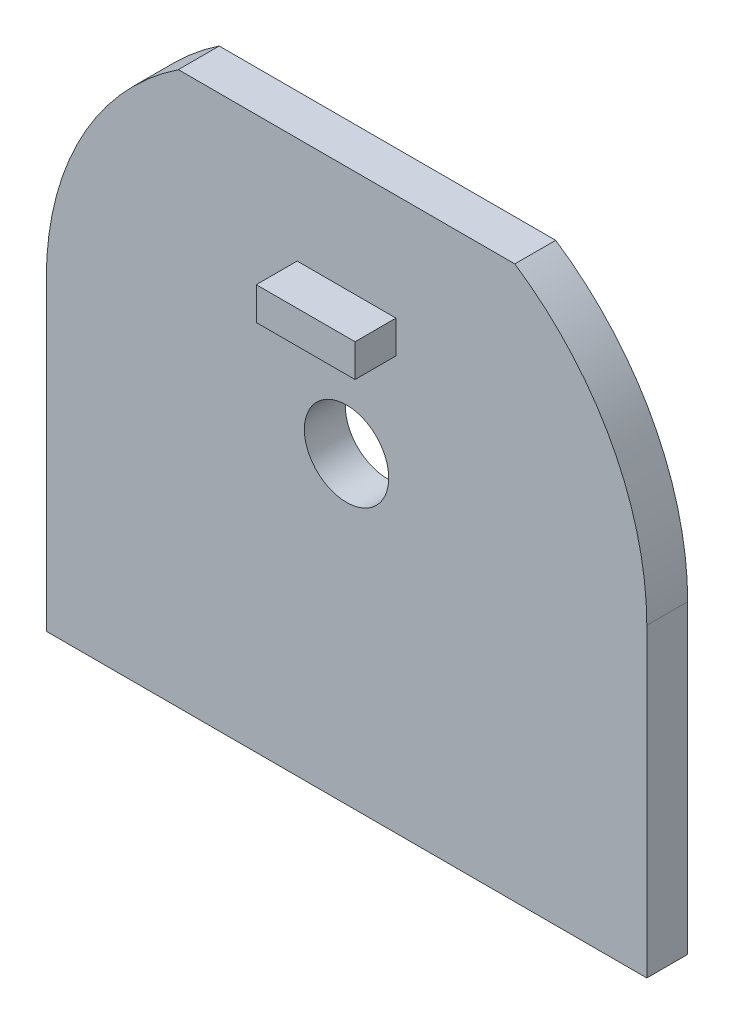
SolidWorks part; units mm, degrees
ref_plane "Front Plane" through (0, 0, 0) normal (0, 0, 1) x (1, 0, 0)
ref_plane "Top Plane" through (0, 0, 0) normal (0, 1, 0) x (1, 0, 0)
ref_plane "Right Plane" through (0, 0, 0) normal (1, 0, 0) x (0, 0, -1)
sketch "Sketch1" plane through (0, 0, 0) normal (0, 0, 1) x (1, 0, 0)
  line L0 (-5.8, 0.6) -> (-5.8, -5.3)
  line L1 (5.8, -5.3) -> (-5.8, -5.3)
  line L5 (5.8, -5.3) -> (-4.5581, 4.1652) construction
  line L6 (4.5581, 4.1652) -> (-5.8, -5.3) construction
  line L7 (5.8, 0.6) -> (5.8, -5.3)
  line L8 (-3.25, 5.3712) -> (3.25, 5.3712)
  line L9 (0, -1000) -> (0, 49000) construction
  circle A0 centre (0, 0.5712) radius 0.815
  arc A1 (-5.8, 0.6) -> (-3.25, 5.3712) centre (-0.0615, 0.6) cw
  arc A2 (5.8, 0.6) -> (3.25, 5.3712) centre (0.0615, 0.6) ccw
  point P0 (0, 0)
  point P8 (-3.25, 5.3712)
  point P9 (3.25, 5.3712)
  point P11 (-5.8, 0.6)
  point P12 (5.8, 0.6)
  point P19 (0, 5.3712)
  point P21 (0, 0)
  point P22 (0, 0)
  point P23 (0, 0)
  point P24 (0, 0)
  point P25 (0, 0)
  dimension "D3" = 1.63
  dimension "D1" = 11.6
  dimension "D7" = 5.9
  dimension "D2" = 6.5
  dimension "D4" = 5.3
  dimension "D5" = 5.3712
  dimension "D6" = 4.8
extrude "Boss-Extrude1" add sketch "Sketch1" along normal blind 0.79
sketch "Sketch2" plane through (0, 0, 0.79) normal (0, 0, 1) x (1, 0, 0)
  line L1 (-0.9541, 2.6836) -> (0.9541, 2.6836)
  line L2 (-0.9541, 2.6836) -> (-0.9541, 3.3164)
  line L3 (-0.9541, 3.3164) -> (0.9541, 3.3164)
  line L4 (0.9541, 2.6836) -> (0.9541, 3.3164)
  line L5 (-0.9541, 2.6836) -> (0.9541, 3.3164) construction
  line L6 (-0.9541, 3.3164) -> (0.9541, 2.6836) construction
  point P0 (0, 3)
  point P5 (0, 0)
  point P7 (0, 0)
  point P8 (0, 0)
  point P9 (0.9541, 2.3656)
  dimension "D1" = 3
  dimension "D2" = 1.9081
  dimension "D3" = 0.6328
extrude "Boss-Extrude2" add sketch "Sketch2" along normal blind 0.79
equation "\"D7@Sketch1\"=5.9mm"
equation "\"D2@Sketch1\"=6.5mm"
equation "\"D6@Sketch1\"=4.8mm"
